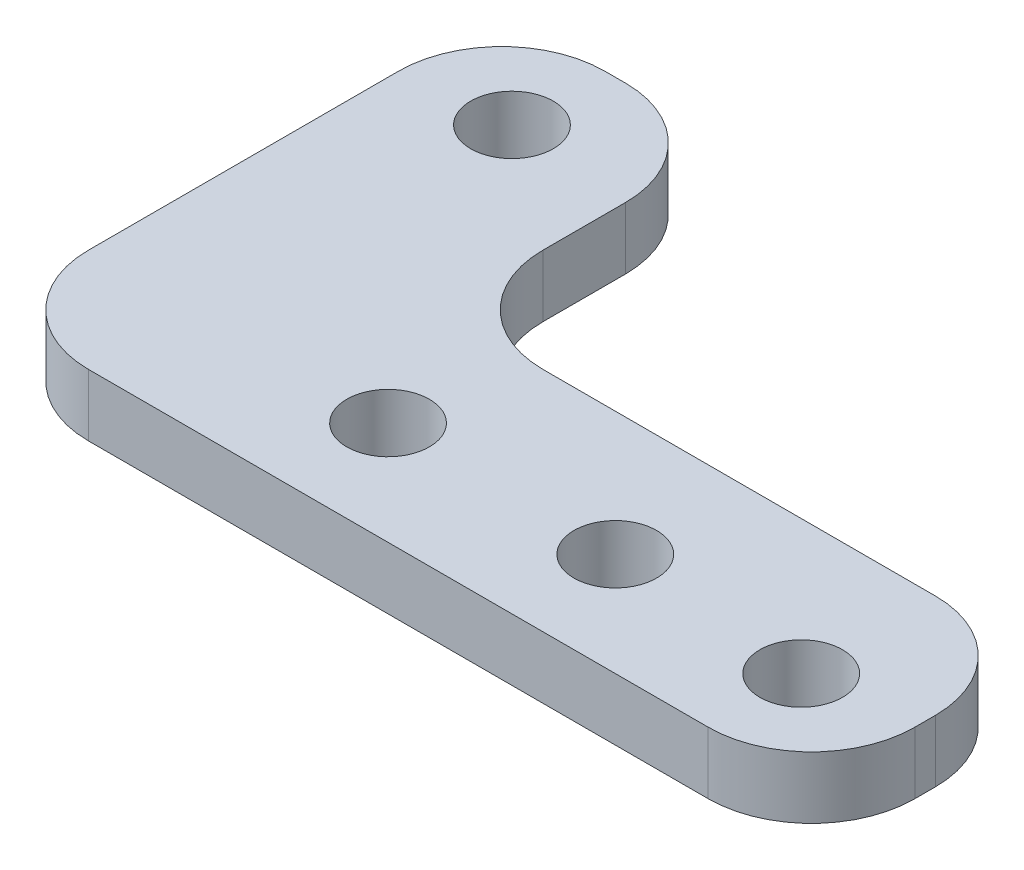
SolidWorks part; units mm, degrees
material "ABS PC"
ref_plane "Front Plane" through (0, 0, 0) normal (0, 0, 1) x (1, 0, 0)
ref_plane "Top Plane" through (0, 0, 0) normal (0, 1, 0) x (1, 0, 0)
ref_plane "Right Plane" through (0, 0, 0) normal (1, 0, 0) x (0, 0, -1)
sketch "Sketch1" plane through (0, 0, 0) normal (0, 1, 0) x (1, 0, 0)
  line L1 (20, -12.5) -> (-20, -12.5)
  line L2 (20, -12.5) -> (20, 12.5)
  line L3 (20, 12.5) -> (-20, 12.5)
  line L4 (-20, -12.5) -> (-20, 12.5)
  line L5 (20, -12.5) -> (-20, 12.5) construction
  line L6 (20, 12.5) -> (-20, -12.5) construction
  point P0 (0, 0)
  dimension "D1" = 25
  dimension "D2" = 40
extrude "Boss-Extrude1" add sketch "Sketch1" along normal blind 3
hole_wizard "Ø4.0 (4) Diameter Hole1" positions "Sketch2" profile "Sketch3" hole size "Ø4.0" standard "ANSI Metric" end condition through all
sketch "Sketch2" plane through (0, 3, 0) normal (0, 1, 0) x (1, 0, 0)
  line L1 (15, -8) -> (-15, -8)
  line L2 (15, -8) -> (15, 8)
  line L3 (15, 8) -> (-15, 8)
  line L4 (-15, -8) -> (-15, 8)
  line L5 (15, -8) -> (-15, 8) construction
  line L6 (15, 8) -> (-15, -8) construction
  point P2 (-15, 8)
  point P5 (15, -8)
  dimension "D1" = 16
  dimension "D2" = 30
sketch "Sketch3" plane through (-15, 3, -8) normal (1, 0, 0) x (0, 0, 1)
  line L0 (0, 0) -> (0, 3)
  line L1 (0, 3) -> (2, 3)
  line L2 (2, 3) -> (2, 0)
  line L5 (2, 0) -> (0, 0)
  line L11 (0, -6.35) -> (0, 107.95) construction
  dimension "Thru Hole Dia." = 4
  dimension "Thru Hole Depth" = 3
sketch "Sketch4" plane through (0, 3, 0) normal (0, 1, 0) x (1, 0, 0)
  line L0 (-20, -12.5) -> (20, -12.5) construction
  line L1 (9, -7.5) -> (-9, -7.5)
  line L2 (9, -7.5) -> (9, -12.5)
  line L3 (9, -12.5) -> (-9, -12.5)
  line L4 (-9, -7.5) -> (-9, -12.5)
  line L5 (9, -7.5) -> (-9, -12.5) construction
  line L6 (9, -12.5) -> (-9, -7.5) construction
  line L7 (0, -10) -> (0, 0) construction
  point P0 (0, -10)
  dimension "D1" = 18
  dimension "D2" = 5
extrude "Cut-Extrude1" [suppressed] cut sketch "Sketch4" against normal blind 3
hole_wizard "Ø4.0 (4) Diameter Hole2" positions "Sketch7" profile "Sketch8" hole size "Ø4.0" standard "ANSI Metric" end condition through all
sketch "Sketch7" plane through (0, 3, 0) normal (0, 1, 0) x (1, 0, 0)
  line L0 (0, 18.0075) -> (0, 15.2248) construction
  line L2 (-20, -12.5) -> (20, -12.5) construction
  point P0 (-5.5, -7.5)
  point P6 (0, 0)
  point P7 (5.5, -7.5)
  dimension "D1" = 11
  dimension "D2" = 5
sketch "Sketch8" plane through (-5.5, 3, 7.5) normal (1, 0, 0) x (0, 0, 1)
  line L0 (0, 0) -> (0, 3)
  line L1 (0, 3) -> (2, 3)
  line L2 (2, 3) -> (2, 0)
  line L5 (2, 0) -> (0, 0)
  line L11 (0, -6.35) -> (0, 107.95) construction
  dimension "Thru Hole Dia." = 4
  dimension "Thru Hole Depth" = 3
sketch "Sketch10" plane through (0, 3, 0) normal (0, 1, 0) x (1, 0, 0)
  line L0 (-9, 12.5) -> (-9, -1.5)
  line L1 (20, 12.5) -> (-20, 12.5) construction
  line L2 (-9, -1.5) -> (20, -1.5)
  line L3 (20, -12.5) -> (20, 12.5) construction
  line L4 (20, -1.5) -> (20, 12.5)
  line L5 (20, 12.5) -> (-9, 12.5)
  circle A0 centre (-15, 8) radius 2 construction
  circle A1 centre (5.5, -7.5) radius 2 construction
  dimension "D1" = 6
  dimension "D2" = 6
extrude "Cut-Extrude2" cut sketch "Sketch10" against normal blind 3
fillet "Fillet2" radius 5 6 edges at (20, 1.5, 1.5) (20, 1.5, 12.5) (-20, 1.5, -12.5) (-9, 1.5, -12.5) (-9, 1.5, 1.5) (-20, 1.5, 12.5)
